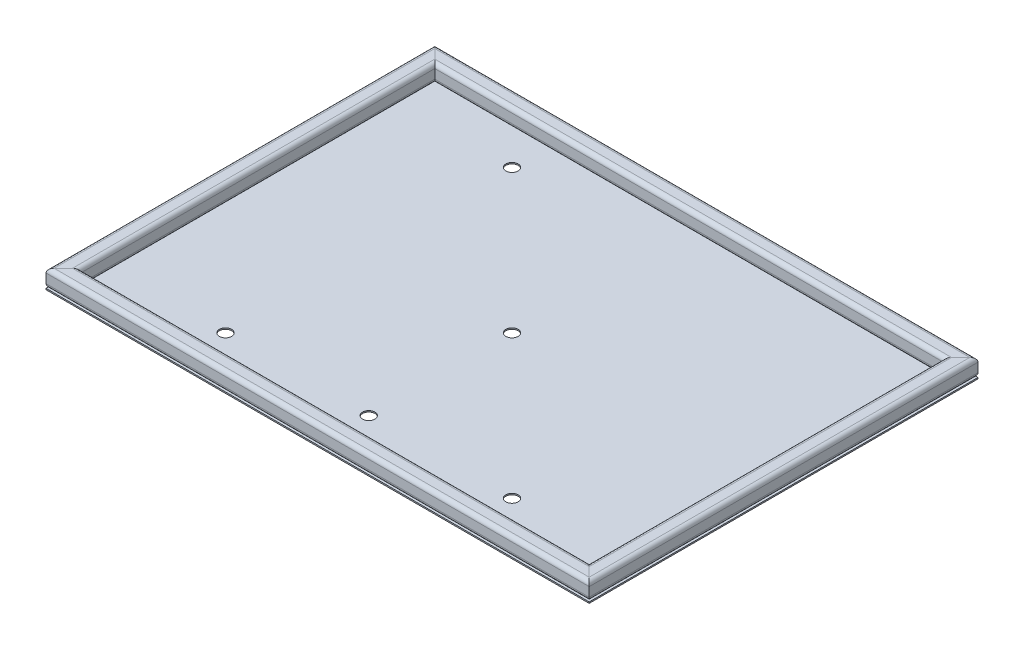
SolidWorks part; units mm, degrees
ref_plane "Alzado" through (0, 0, 0) normal (0, 0, 1) x (1, 0, 0)
ref_plane "Planta" through (0, 0, 0) normal (0, 1, 0) x (1, 0, 0)
ref_plane "Vista lateral" through (0, 0, 0) normal (1, 0, 0) x (0, 0, -1)
sketch "Croquis1" plane through (0, 0, 0) normal (0, 1, 0) x (1, 0, 0)
  line L1 (-398.2, 285) -> (398.2, 285)
  line L2 (-398.2, 285) -> (-398.2, -285)
  line L3 (-398.2, -285) -> (398.2, -285)
  line L4 (398.2, 285) -> (398.2, -285)
  line L5 (-398.2, 285) -> (398.2, -285) construction
  line L6 (-398.2, -285) -> (398.2, 285) construction
  point P0 (0, 0)
  dimension "D1" = 570
  dimension "D2" = 796.4
other "Tubo cuadrado 2 X 2 X 0.25(1)"
ref_plane "Plano1" through (-385.5, 12.7, -285) normal (0, 0, 1) x (1, 0, 0)
sketch "Sketch1" plane through (-385.5, 12.7, -285) normal (0, 0, 1) x (1, 0, 0)
  line L0 (-6.7, -9.7) -> (6.7, -9.7)
  line L1 (-9.7, -6.7) -> (-9.7, 6.7)
  line L2 (6.7, 9.7) -> (-6.7, 9.7)
  line L3 (9.7, 6.7) -> (9.7, -6.7)
  line L4 (-6.7, -12.7) -> (6.7, -12.7)
  line L5 (-12.7, -6.7) -> (-12.7, 6.7)
  line L6 (6.7, 12.7) -> (-6.7, 12.7)
  line L7 (12.7, 6.7) -> (12.7, -6.7)
  line L8 (0, 0) -> (9.7, 0) construction
  line L9 (0, 0) -> (0, 9.7) construction
  arc A0 (12.7, 6.7) -> (6.7, 12.7) centre (6.7, 6.7) ccw
  arc A1 (6.7, -12.7) -> (12.7, -6.7) centre (6.7, -6.7) ccw
  arc A2 (-12.7, -6.7) -> (-6.7, -12.7) centre (-6.7, -6.7) ccw
  arc A3 (-6.7, 12.7) -> (-12.7, 6.7) centre (-6.7, 6.7) ccw
  arc A4 (-6.7, 9.7) -> (-9.7, 6.7) centre (-6.7, 6.7) ccw
  arc A5 (9.7, 6.7) -> (6.7, 9.7) centre (6.7, 6.7) ccw
  arc A6 (6.7, -9.7) -> (9.7, -6.7) centre (6.7, -6.7) ccw
  arc A7 (-9.7, -6.7) -> (-6.7, -9.7) centre (-6.7, -6.7) ccw
  point P3 (0, 12.7)
  point P4 (12.7, 0)
  point P5 (0, -12.7)
  point P6 (-12.7, 0)
  point P7 (-12.7, 12.7)
  point P8 (-12.7, -12.7)
  point P33 (0, 0)
  point P35 (12.7, -12.7)
  point P36 (12.7, 12.7)
  point P37 (0, 0)
  dimension "D1" = 6
  dimension "Thickness" = 3
  dimension "V_leg" = 25.4
sketch "Croquis3" plane through (0, 0, 0) normal (0, -1, 0) x (1, 0, 0)
  line L1 (398.2, 285) -> (-398.2, 285)
  line L2 (398.2, 285) -> (398.2, -285)
  line L3 (398.2, -285) -> (-398.2, -285)
  line L4 (-398.2, 285) -> (-398.2, -285)
  line L5 (398.2, 285) -> (-398.2, -285) construction
  line L6 (398.2, -285) -> (-398.2, 285) construction
  point P0 (0, 0)
extrude "Saliente-Extruir1" add sketch "Croquis3" along normal blind 1.9 separate body
ref_plane "Plano2" through (0, 0, 210) normal (0, 0, 1) x (1, 0, 0)
sketch "Croquis4" plane through (0, -1128.704, 0) normal (0, 1, 0) x (1, 0, 0)
  circle A0 centre (2010, 436.4137) radius 8.0354
sketch "Croquis5" plane through (0, 0, 0) normal (0, 1, 0) x (1, 0, 0)
  circle A0 centre (233, -210.2449) radius 3.1562
  circle A1 centre (210, -210) radius 7.8426
  circle A2 centre (187, -209.7551) radius 3.1812
  circle A3 centre (0, -210) radius 7.9375
  circle A4 centre (-23, -209.7551) radius 3.175
  circle A5 centre (23, -210.2449) radius 3.244
  circle A6 centre (-233, -209.7551) radius 3.175
  circle A7 centre (-210, -210) radius 7.9375
  circle A8 centre (-187, -210.2449) radius 3.175
sketch "Croquis6" plane through (0, -1.9, 0) normal (0, -1, 0) x (1, 0, 0)
  line L0 (-398.2, -210) -> (-210, -210) construction
  line L1 (-398.2, 285) -> (-398.2, -285) construction
  line L2 (-210, -210) -> (-210, -285) construction
  line L3 (-398.2, -285) -> (398.2, -285) construction
  line L4 (-398.2, 210) -> (-210, 210) construction
  line L5 (-398.2, 285) -> (-398.2, -285) construction
  line L6 (-210, 210) -> (-210, 285) construction
  line L7 (398.2, 285) -> (-398.2, 285) construction
  line L8 (-210, 210) -> (0, 210) construction
  line L9 (0, 210) -> (210, 210) construction
  circle A0 centre (0, 0) radius 9
  circle A1 centre (210, 210) radius 9
  circle A2 centre (0, 210) radius 9
  circle A3 centre (-210, 210) radius 9
  circle A4 centre (-210, -210) radius 9
  dimension "D7" = 18
  dimension "D8" = 18
  dimension "D9" = 18
  dimension "D10" = 18
  dimension "D11" = 18
  dimension "D1" = 75
  dimension "D2" = 188.2
  dimension "D3" = 188.2
  dimension "D4" = 75
  dimension "D5" = 210
  dimension "D6" = 210
extrude "Cortar-Extruir2" cut sketch "Croquis6" against normal blind 10
sketch "Croquis7" plane through (0, -1.9, 0) normal (0, -1, 0) x (1, 0, 0)
  line L0 (9, 210) -> (0, 210) construction
  line L1 (0, 210) -> (0, 0) construction
  circle A0 centre (0, 210) radius 9 construction
